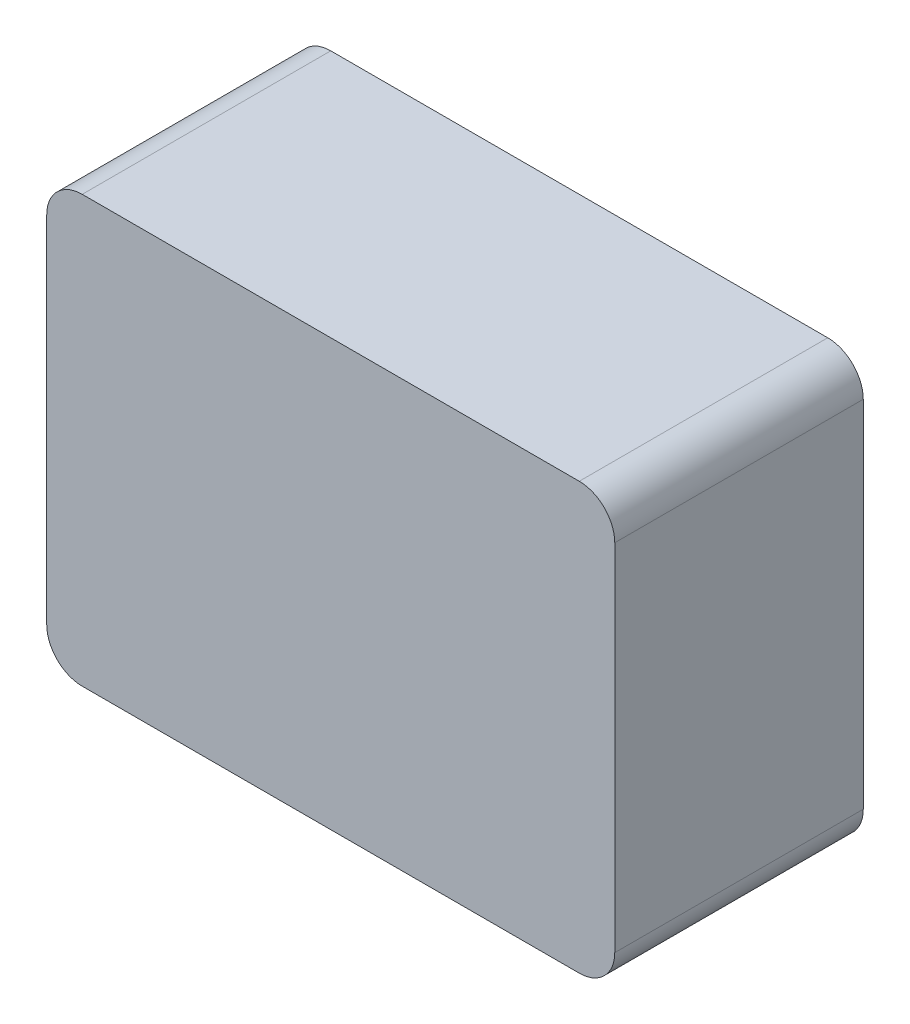
SolidWorks part; units mm, degrees
ref_plane "Front Plane" through (0, 0, 0) normal (0, 0, 1) x (1, 0, 0)
ref_plane "Top Plane" through (0, 0, 0) normal (0, 1, 0) x (1, 0, 0)
ref_plane "Right Plane" through (0, 0, 0) normal (1, 0, 0) x (0, 0, -1)
sketch "Sketch1" plane through (0, 0, 0) normal (0, 0, 1) x (1, 0, 0)
  line L1 (-40, -30) -> (40, -30)
  line L2 (-40, -30) -> (-40, 30)
  line L3 (-40, 30) -> (40, 30)
  line L4 (40, -30) -> (40, 30)
  line L5 (-40, -30) -> (40, 30) construction
  line L6 (-40, 30) -> (40, -30) construction
  point P0 (0, 0)
  dimension "D1" = 80
  dimension "D2" = 60
extrude "Boss-Extrude5" add sketch "Sketch1" against normal blind 5
sketch "Sketch4" plane through (0, 0, -5) normal (0, 0, -1) x (-1, 0, 0)
  line L1 (40, -30) -> (-40, -30) construction
  line L2 (-37.5, -27.5) -> (37.5, -27.5)
  line L3 (-37.5, -27.5) -> (-37.5, 27.5)
  line L4 (-37.5, 27.5) -> (37.5, 27.5)
  line L5 (37.5, -27.5) -> (37.5, 27.5)
  line L6 (-37.5, -27.5) -> (37.5, 27.5) construction
  line L7 (-37.5, 27.5) -> (37.5, -27.5) construction
  line L8 (40, 30) -> (40, -30) construction
  line L9 (-40, -30) -> (-40, 30) construction
  line L10 (-40, 30) -> (40, 30) construction
  line L11 (40, -30) -> (-40, -30)
  line L12 (40, 30) -> (40, -30)
  line L13 (-40, -30) -> (-40, 30)
  line L14 (-40, 30) -> (40, 30)
  point P2 (0, 0)
  dimension "D1" = 75
  dimension "D2" = 55
extrude "Boss-Extrude6" add sketch "Sketch4" along normal blind 30
fillet "Fillet2" radius 5 4 edges at (-40, -30, -17.5) (-40, 30, -17.5) (40, 30, -17.5) (40, -30, -17.5)
sketch "Sketch5" plane through (0, 30, 0) normal (0, 1, 0) x (1, 0, 0)
  line L0 (-35, 35) -> (-35, 17.5)
  line L1 (-35, 35) -> (-35, 0) construction
  line L3 (-24.5711, 24.5711) -> (-10.4289, 10.4289)
  line L4 (-17.5, 27.5) -> (-17.5, 7.5)
  line L5 (-27.5, 17.5) -> (-7.5, 17.5)
  line L6 (-10.4289, 24.5711) -> (-24.5711, 10.4289)
  line L7 (-7.5, 17.5) -> (-27.5, 17.5)
  line L8 (-10.4289, 10.4289) -> (-24.5711, 24.5711)
  line L9 (-17.5, 7.5) -> (-17.5, 27.5)
  line L10 (-24.5711, 10.4289) -> (-10.4289, 24.5711)
  circle A3 centre (-17.5, 17.5) radius 5
  circle A4 centre (-17.5, 17.5) radius 7.5
  circle A5 centre (-17.5, 17.5) radius 2.5
  circle A6 centre (-17.5, 17.5) radius 10
  point P29 (-17.5, 17.5)
  dimension "D3" = 20
  dimension "D4" = 15
  dimension "D5" = 10
  dimension "D6" = 5
  dimension "D1" = 17.5
  dimension "D2" = 17.5
  dimension "D7" = 8
